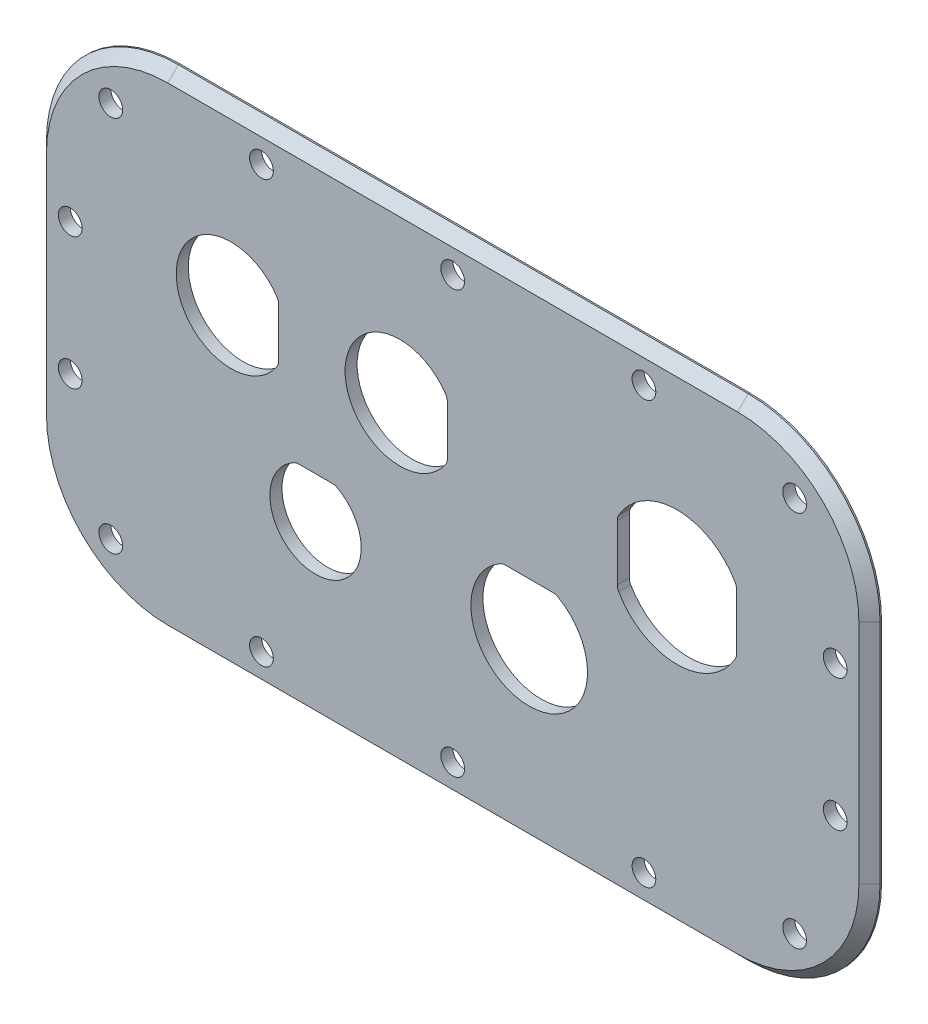
SolidWorks part; units mm, degrees
material "6061-T6 (SS)"
ref_plane "Front" through (0, 0, 0) normal (0, 0, 1) x (1, 0, 0)
ref_plane "Top" through (0, 0, 0) normal (0, 1, 0) x (1, 0, 0)
ref_plane "Right" through (0, 0, 0) normal (1, 0, 0) x (0, 0, -1)
sketch "Sketch1" plane through (0, 0, 0) normal (0, 0, 1) x (1, 0, 0)
  line L1 (79, 46.5) -> (-79, 46.5)
  line L2 (79, 46.5) -> (79, -46.5)
  line L3 (79, -46.5) -> (-79, -46.5)
  line L4 (-79, 46.5) -> (-79, -46.5)
  line L5 (79, 46.5) -> (-79, -46.5) construction
  line L6 (79, -46.5) -> (-79, 46.5) construction
  point P0 (0, 0)
  dimension "D1" = 158
  dimension "D2" = 93
extrude "Boss-Extrude1" add sketch "Sketch1" along normal mid plane 2.286
fillet "Fillet1" radius 25 4 edges at (-79, 46.5, 0) (79, -46.5, 0) (-79, -46.5, 0) (79, 46.5, 0)
hole_wizard "M4 Clearance Hole1" positions "Sketch3" profile "Sketch4" hole size "M4" standard "ANSI Metric" end condition up to next
sketch "Sketch3" plane through (0, 0, 1.143) normal (0, 0, 1) x (1, 0, 0)
  line L1 (-72.5, 40) -> (72.5, 40) construction
  line L2 (-72.5, 40) -> (-72.5, -40) construction
  line L3 (-72.5, -40) -> (72.5, -40) construction
  line L4 (72.5, 40) -> (72.5, -40) construction
  line L5 (-72.5, 40) -> (72.5, -40) construction
  line L6 (-72.5, -40) -> (72.5, 40) construction
  line L7 (0, 46.5) -> (0, 0) construction
  line L9 (0, 0) -> (-79, 0) construction
  line L11 (-36.25, 40) -> (-36.25, -40) construction
  line L13 (36.25, 40) -> (36.25, -40) construction
  line L14 (-79, 21.5) -> (-79, -21.5) construction
  line L15 (54, 46.5) -> (-54, 46.5) construction
  line L16 (-72.5, 12.5) -> (72.5, 12.5) construction
  line L18 (-72.5, -12.5) -> (72.5, -12.5) construction
  arc A0 (-72.5, 20) -> (-52.5, 40) centre (-52.5, 20) cw construction
  arc A1 (-72.5, -20) -> (-52.5, -40) centre (-52.5, -20) ccw construction
  arc A2 (52.5, -40) -> (72.5, -20) centre (52.5, -20) ccw construction
  arc A3 (72.5, 20) -> (52.5, 40) centre (52.5, 20) ccw construction
  point P212 (0, 40)
  point P229 (0, -40)
  point P231 (-36.25, -40)
  point P233 (-36.25, 40)
  point P235 (36.25, 40)
  point P237 (36.25, -40)
  point P279 (-64.8141, 35.7595)
  point P281 (-64.8141, -35.7595)
  point P283 (64.8141, -35.7595)
  point P285 (64.8141, 35.7595)
  point P304 (-72.5, 12.5)
  point P306 (-72.5, -12.5)
  point P308 (72.5, -12.5)
  point P310 (72.5, 12.5)
  dimension "D5" = 20
  dimension "D2" = 145
  dimension "D3" = 36.25
  dimension "D4" = 36.25
  dimension "D1" = 80
  dimension "D6" = 12.5
  dimension "D7" = 12.5
sketch "Sketch4" plane through (72.5, 12.5, 1.143) normal (1, 0, 0) x (0, -1, 0)
  line L0 (0, 0) -> (0, 2.286)
  line L1 (0, 2.286) -> (2.25, 2.286)
  line L2 (2.25, 2.286) -> (2.25, 0)
  line L5 (2.25, 0) -> (0, 0)
  line L11 (0, -6.35) -> (0, 107.95) construction
  dimension "Thru Hole Dia." = 4.5
  dimension "Thru Hole Depth" = 2.286
chamfer "Chamfer2" distance 2 angle 45 8 edges at (71.6777, 39.1777, 1.143) (0, 46.5, 1.143) (79, 0, 1.143) (-71.6777, 39.1777, 1.143) (71.6777, -39.1777, 1.143) (-79, 0, 1.143) (0, -46.5, 1.143) (-71.6777, -39.1777, 1.143)
sketch "Sketch6" plane through (0, 0, 1.143) normal (0, 0, 1) x (1, 0, 0)
  line L0 (-62.5, 10) -> (62.5, 10) construction
  line L1 (-26, -13.5) -> (-26, 14) construction
  line L3 (-42, 14) -> (-10, 14) construction
  line L4 (62.5, -13.5) -> (-62.5, -13.5) construction
  line L7 (50.5, -30) -> (-50.5, -30) construction
  line L8 (-26, -28.5) -> (-13.0096, -21) construction
  line L9 (-13.0096, -21) -> (-13.0096, -6) construction
  line L10 (-13.0096, -6) -> (-26, 1.5) construction
  line L11 (-26, 1.5) -> (-38.9904, -6) construction
  line L12 (-38.9904, -6) -> (-38.9904, -21) construction
  line L13 (-38.9904, -21) -> (-26, -28.5) construction
  line L20 (62.5, -18) -> (62.5, 18) construction
  line L21 (50.5, 30) -> (-50.5, 30) construction
  line L22 (-62.5, -18) -> (-62.5, 18) construction
  line L23 (62.5, -30) -> (-62.5, 30) construction
  line L24 (62.5, 30) -> (-62.5, -30) construction
  circle A0 centre (-42, 14) radius 15 construction
  circle A1 centre (-10, 14) radius 15 construction
  circle A2 centre (-26, -13.5) radius 12.5 construction
  circle A4 centre (14.5, -12.5) radius 16 construction
  circle A5 centre (42.5, 10) radius 18.5 construction
  circle A8 centre (-26, -13.5) radius 12.9904 construction
  circle A11 centre (-26, -13.5) radius 15 construction
  arc A12 (-62.5, -18) -> (-50.5, -30) centre (-50.5, -18) ccw construction
  arc A13 (50.5, -30) -> (62.5, -18) centre (50.5, -18) ccw construction
  arc A14 (62.5, 18) -> (50.5, 30) centre (50.5, 18) ccw construction
  arc A15 (-50.5, 30) -> (-62.5, 18) centre (-50.5, 18) ccw construction
  point P37 (0, 0)
  dimension "D2" = 30
  dimension "D3" = 32
  dimension "D4" = 37
  dimension "D18" = 12
  dimension "D11" = 30
  dimension "D14" = 25
  dimension "D5" = 20
  dimension "D6" = 32
  dimension "D7" = 10
  dimension "D8" = 13.5
  dimension "D9" = 10
  dimension "D10" = 4
  dimension "D12" = 1
  dimension "D13" = 28
  dimension "D16" = 125
  dimension "D17" = 60
sketch "Sketch7" plane through (0, 0, 1.143) normal (0, 0, 1) x (1, 0, 0)
  line L0 (-33, 19.2115) -> (-33, 8.7885)
  line L1 (-29.6332, -5.65) -> (-22.3668, -5.65)
  line L2 (-1, 19.2115) -> (-1, 8.7885)
  line L4 (31.197, 15.7907) -> (31.197, 4.2093)
  line L6 (53.803, 15.7907) -> (53.803, 4.2093)
  line L8 (9.492, -2.65) -> (19.508, -2.65)
  arc A0 (-29.6332, -5.65) -> (-22.3668, -5.65) centre (-26, -13.5) ccw
  arc A2 (9.492, -2.65) -> (19.508, -2.65) centre (14.5, -12.5) ccw
  arc A3 (-33, 19.2115) -> (-33, 8.7885) centre (-42, 14) ccw
  arc A4 (-1, 19.2115) -> (-1, 8.7885) centre (-10, 14) ccw
  arc A5 (31.197, 4.2093) -> (53.803, 4.2093) centre (42.5, 10) ccw
  arc A6 (53.803, 15.7907) -> (31.197, 15.7907) centre (42.5, 10) ccw
  point P1 (14.5, -23.55)
  point P4 (-26, -22.15)
  point P10 (-52.4, 14)
  dimension "D1" = 10.4
  dimension "D4" = 12.7
  dimension "D5" = 8.65
  dimension "D6" = 11.05
  dimension "D2" = 19.4
  dimension "D3" = 22.606
  dimension "D7" = 16.5
  dimension "D8" = 20.9
extrude "Cut-Extrude1" cut sketch "Sketch7" against normal up to next
fillet "Fillet2" radius 2 12 edges at (-29.6332, -5.65, 0) (-22.3668, -5.65, 0) (-33, 8.7885, 0) (-33, 19.2115, 0) (-1, 19.2115, 0) (-1, 8.7885, 0) (9.492, -2.65, 0) (19.508, -2.65, 0) (53.803, 15.7907, 0) (53.803, 4.2093, 0) (31.197, 4.2093, 0) (31.197, 15.7907, 0)
equation "\"D3@Sketch3\"=\"D2@Sketch3\"/4"
equation "\"D4@Sketch3\"=\"D3@Sketch3\""
